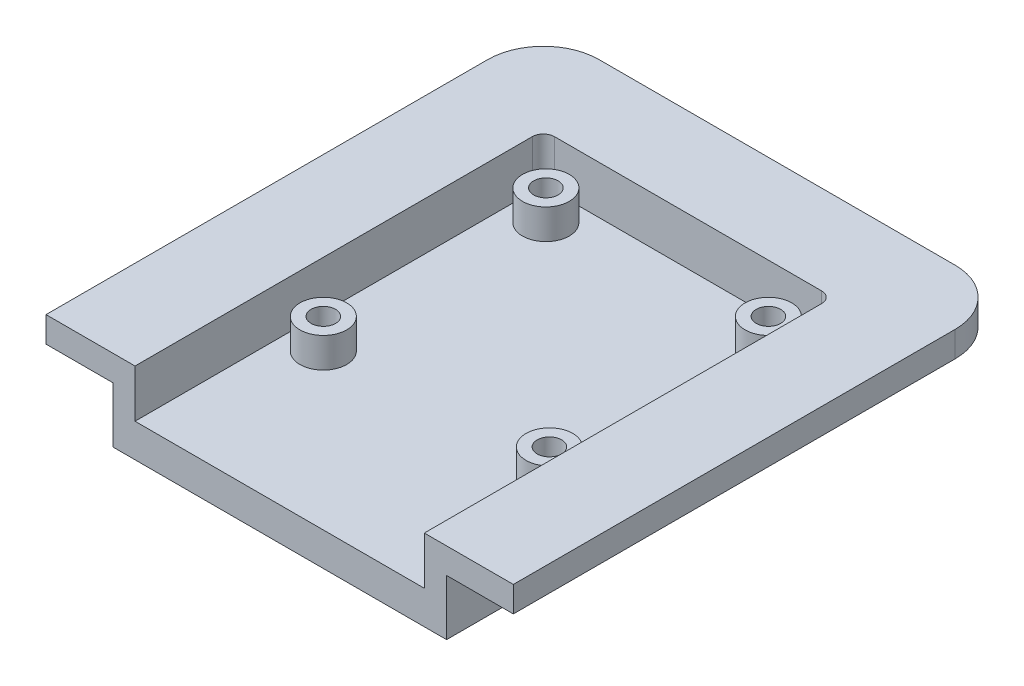
SolidWorks part; units mm, degrees
ref_plane "Front Plane" through (0, 0, 0) normal (0, 0, 1) x (1, 0, 0)
ref_plane "Top Plane" through (0, 0, 0) normal (0, 1, 0) x (1, 0, 0)
ref_plane "Right Plane" through (0, 0, 0) normal (1, 0, 0) x (0, 0, -1)
sketch "Sketch1" plane through (0, 0, 0) normal (0, 1, 0) x (1, 0, 0)
  line L0 (0, 0) -> (0, 19.35) construction
  line L1 (-15, 19.35) -> (15, 19.35)
  line L2 (-15, 19.35) -> (-15, -19.35)
  line L3 (-15, -19.35) -> (15, -19.35)
  line L4 (15, 19.35) -> (15, -19.35)
  line L5 (0, 0) -> (15, 0) construction
  line L7 (-13, 17.35) -> (13, 17.35) construction
  line L8 (-13, 17.35) -> (-13, -17.35) construction
  line L9 (-13, -17.35) -> (13, -17.35) construction
  line L10 (13, 17.35) -> (13, -17.35) construction
  dimension "D1" = 30
  dimension "D2" = 38.7
  dimension "D3" = 2
  dimension "D4" = 2
  dimension "D5" = 2
  dimension "D6" = 2
extrude "Boss-Extrude1" add sketch "Sketch1" along normal blind 3
sketch "Sketch2" plane through (0, 3, 0) normal (0, 1, 0) x (1, 0, 0)
  line L0 (-13, 17.35) -> (-13, -19.35)
  line L1 (-15, -19.35) -> (15, -19.35) construction
  line L2 (-13, -19.35) -> (-15, -19.35)
  line L3 (-15, -19.35) -> (-15, 19.35)
  line L4 (-15, 19.35) -> (15, 19.35)
  line L5 (15, 19.35) -> (15, -19.35)
  line L6 (15, -19.35) -> (13, -19.35)
  line L7 (13, -19.35) -> (13, 17.35)
  line L8 (13, 17.35) -> (-13, 17.35)
extrude "Boss-Extrude2" add sketch "Sketch2" along normal blind 4.3
fillet "Fillet1" radius 1 2 edges at (13, 5.15, -17.35) (-13, 5.15, -17.35)
sketch "Sketch3" plane through (0, 3, 0) normal (0, 1, 0) x (1, 0, 0)
  line L0 (0, 0) -> (0, 19.35) construction
  circle A0 centre (-10, 14.5731) radius 1.1
  circle A1 centre (10, 14.5731) radius 1.1
  circle A2 centre (-10, -5.4269) radius 1.1
  circle A3 centre (10.3175, -5.4269) radius 1.1
  point P10 (0, 0)
  point P11 (0, 0)
  point P12 (0, 0)
  dimension "D4" = 2.2
  dimension "D1" = 10
  dimension "D2" = 10
  dimension "D3" = 20
extrude "Cut-Extrude1" cut sketch "Sketch3" against normal through all
sketch "Sketch4" plane through (0, 3, 0) normal (0, 1, 0) x (1, 0, 0)
  circle A0 centre (-10, 14.5731) radius 1.1
  circle A1 centre (-10, 14.5731) radius 2.1
  circle A2 centre (10, 14.5731) radius 1.1
  circle A3 centre (10, 14.5731) radius 2.1
  circle A4 centre (10.3175, -5.4269) radius 1.1
  circle A5 centre (10.3175, -5.4269) radius 2.1
  circle A6 centre (-10, -5.4269) radius 1.1
  circle A7 centre (-10, -5.4269) radius 2.1
  circle A8 centre (-10, 14.5731) radius 1.1 construction
  dimension "D1" = 1
extrude "Boss-Extrude3" add sketch "Sketch4" along normal blind 2.7
sketch "Sketch5" plane through (0, 0, 0) normal (0, 1, 0) x (1, 0, 0)
  line L0 (-15, 19.35) -> (15, 19.35) construction
  line L1 (-21, 25.35) -> (21, 25.35)
  line L2 (-21, 25.35) -> (-21, -19.35)
  line L3 (-21, -19.35) -> (21, -19.35) construction
  line L4 (21, 25.35) -> (21, -19.35)
  line L5 (-15, 19.35) -> (-15, -19.35) construction
  line L6 (-15, -19.35) -> (15, -19.35) construction
  line L7 (15, 19.35) -> (15, -19.35) construction
  line L8 (-15, -19.35) -> (-15, 19.35)
  line L9 (-15, 19.35) -> (15, 19.35)
  line L10 (15, 19.35) -> (15, -19.35)
  line L11 (-21, -19.35) -> (-15, -19.35)
  line L12 (15, -19.35) -> (21, -19.35)
  dimension "D1" = 6
  dimension "D2" = 6
  dimension "D3" = 0
  dimension "D4" = 6
extrude "Boss-Extrude4" add sketch "Sketch5" along normal up to surface (2.3 mm away) from offset 5 up to face at (0, 7.3, -2.9114)
fillet "Fillet2" radius 5 2 edges at (21, 6.15, -25.35) (-21, 6.15, -25.35)
